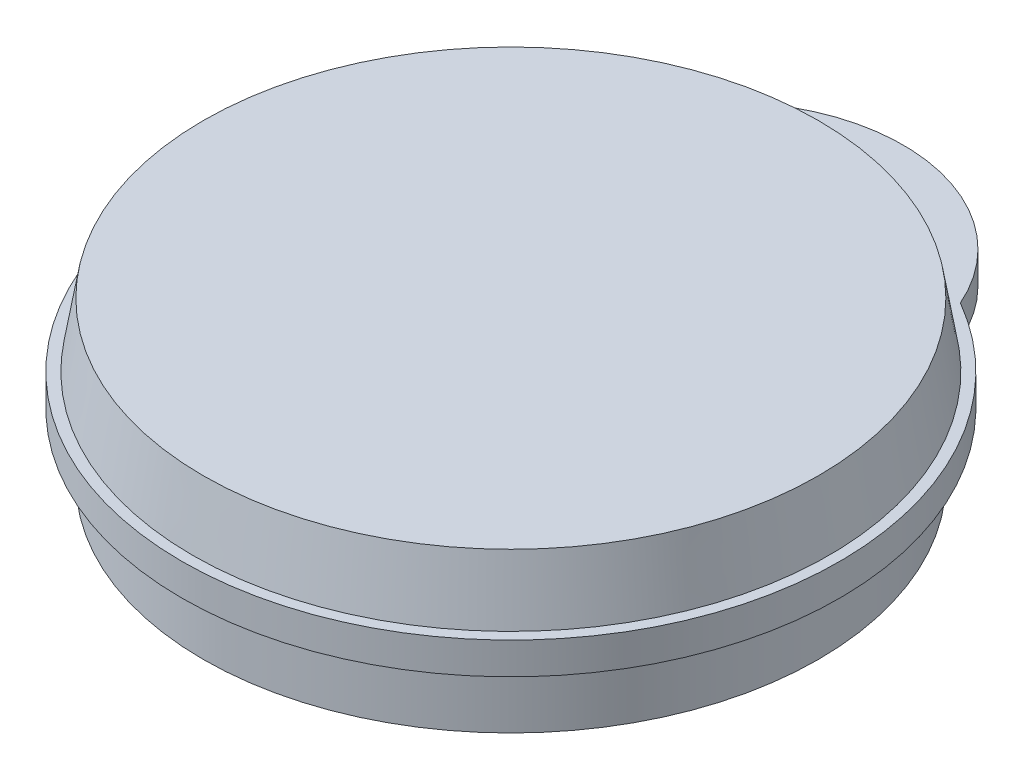
SolidWorks part; units mm, degrees
material "Rubber"
ref_plane "Front Plane" through (0, 0, 0) normal (0, 0, 1) x (1, 0, 0)
ref_plane "Top Plane" through (0, 0, 0) normal (0, 1, 0) x (1, 0, 0)
ref_plane "Right Plane" through (0, 0, 0) normal (1, 0, 0) x (0, 0, -1)
sketch "Sketch1" plane through (0, 0, 0) normal (0, 0, 1) x (1, 0, 0)
  line L0 (0, 0) -> (14.5, 0)
  line L1 (14.5, 0) -> (14.5, 3)
  line L2 (14.5, 3) -> (15.5, 3)
  line L3 (15.5, 3) -> (15.5, 4.5)
  line L4 (15.5, 4.5) -> (15, 4.5)
  line L5 (15, 4.5) -> (14.5, 7.5)
  line L6 (14.5, 7.5) -> (0, 7.5)
  line L7 (0, 7.5) -> (0, 0)
  dimension "D1" = 14.5
  dimension "D2" = 15.5
  dimension "D3" = 14.5
  dimension "D4" = 3
  dimension "D5" = 1.5
  dimension "D6" = 3
  dimension "D7" = 0.5
revolve "Revolve1" add sketch "Sketch1" angle 360 about L7
sketch "Sketch2" plane through (0, 4.5, 0) normal (0, 1, 0) x (1, 0, 0)
  arc A0 (8.0804, 12.6375) -> (-8.0804, 12.6375) centre (0, 10) ccw
  arc A1 (8.0804, 12.6375) -> (-8.0804, 12.6375) centre (0, 0) ccw
  dimension "D1" = 15
  dimension "D2" = 8.5
  dimension "D3" = 10
extrude "Boss-Extrude1" add sketch "Sketch2" against normal up to surface (1.5 mm away) up to face at (0, 3, 15.5)
